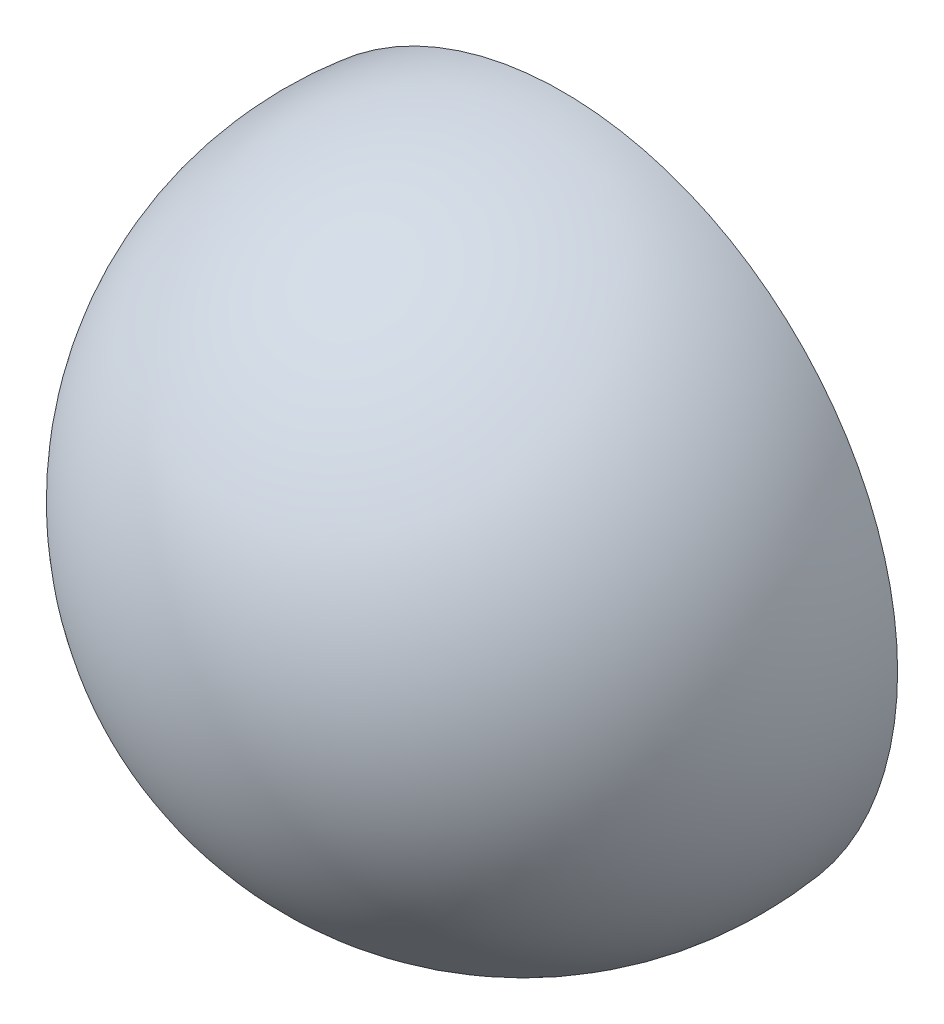
SolidWorks part; units mm, degrees
material "Настроенная пользователем пластмасса"
ref_plane "Спереди" through (0, 0, 0) normal (0, 0, 1) x (1, 0, 0)
ref_plane "Сверху" through (0, 0, 0) normal (0, 1, 0) x (1, 0, 0)
ref_plane "Справа" through (0, 0, 0) normal (1, 0, 0) x (0, 0, -1)
sketch "Эскиз1" plane through (0, 0, 0) normal (0, 1, 0) x (1, 0, 0)
  line L0 (0, 0) -> (0, -4.5)
  line L1 (0, 0) -> (-4, 0)
  line L2 (0, 0) -> (0, -5.1258) construction
  arc A1 (0, -4.5) -> (-4, 0) centre (0, -0.4722) cw
  dimension "D1" = 8
  dimension "D2" = 4.5
revolve "Повернуть1" add sketch "Эскиз1" angle 360 about L2
